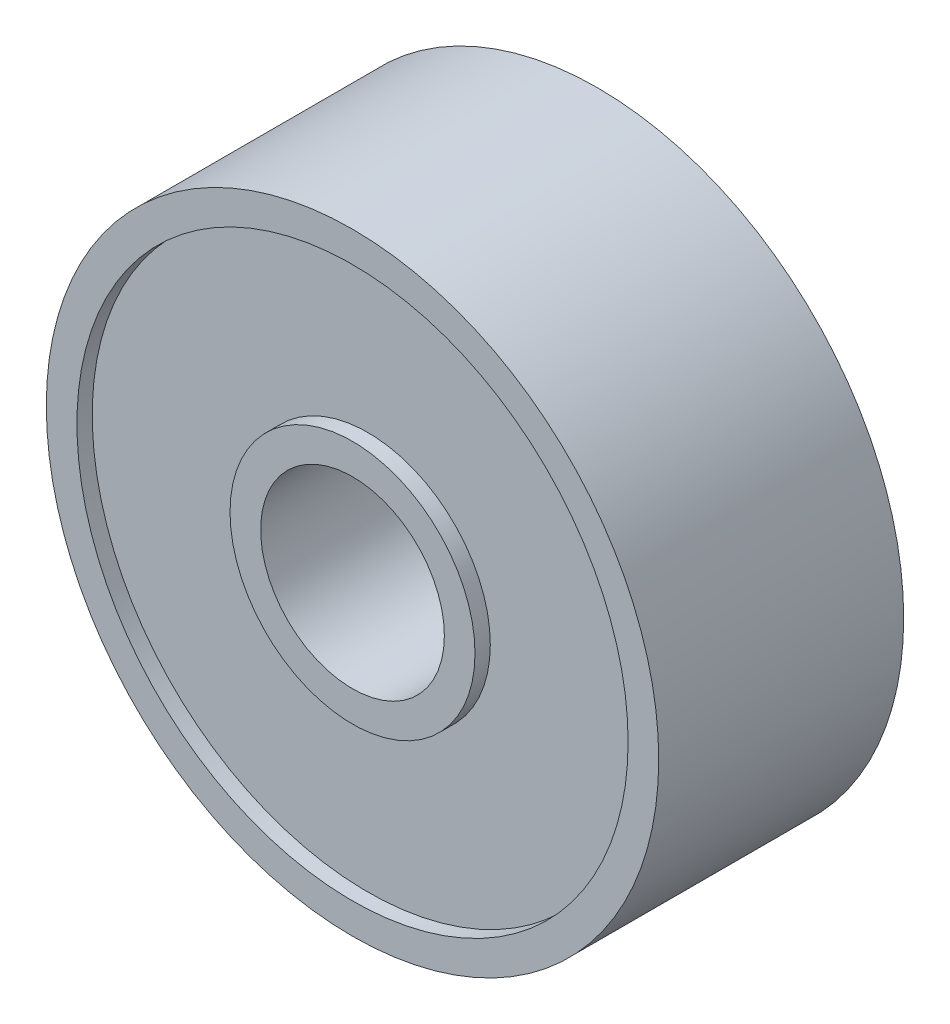
SolidWorks part; units mm, degrees
ref_plane "Front Plane" through (0, 0, 0) normal (0, 0, 1) x (1, 0, 0)
ref_plane "Top Plane" through (0, 0, 0) normal (0, 1, 0) x (1, 0, 0)
ref_plane "Right Plane" through (0, 0, 0) normal (1, 0, 0) x (0, 0, -1)
sketch "Sketch1" plane through (0, 0, 0) normal (0, 0, 1) x (1, 0, 0)
  circle A0 centre (0, 0) radius 1.5
  circle A1 centre (0, 0) radius 5
  dimension "D1" = 10
  dimension "D2" = 3
extrude "Boss-Extrude1" add sketch "Sketch1" along normal mid plane 4
sketch "Sketch2" plane through (0, 0, 2) normal (0, 0, 1) x (1, 0, 0)
  circle A2 centre (0, 0) radius 4.5
  circle A3 centre (0, 0) radius 4.5
  circle A5 centre (0, 0) radius 2
  circle A6 centre (0, 0) radius 2
  dimension "D1" = 0.5
  dimension "D2" = 0.5
extrude "Cut-Extrude1" cut sketch "Sketch2" against normal blind 0.25 contours A3 | A6
mirror "Mirror1" about plane through (0, 0, 0) normal (0, 0, 1) of "Cut-Extrude1"
equation "\"Bearing Internal 'd'\"= 3mm"
equation "\"Bearing External 'd'\"= 10mm"
equation "\"Bearing Width\"= 4mm"
equation "\"D1@Sketch1\"=\"Bearing External 'd'\"''''''"
equation "\"D2@Sketch1\"=\"Bearing Internal 'd'\"''''''"
equation "\"D1@Boss-Extrude1\"=\"Bearing Width\""
